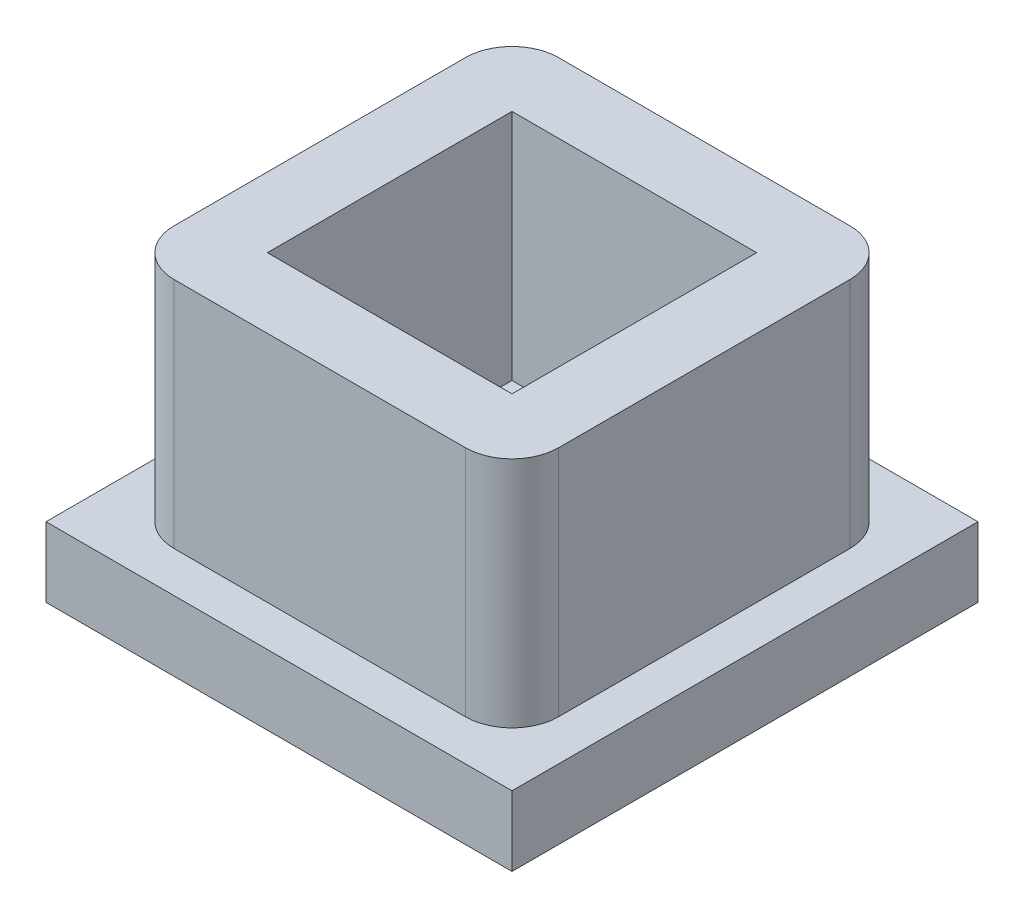
SolidWorks part; units mm, degrees
ref_plane "Front Plane" through (0, 0, 0) normal (0, 0, 1) x (1, 0, 0)
ref_plane "Top Plane" through (0, 0, 0) normal (0, 1, 0) x (1, 0, 0)
ref_plane "Right Plane" through (0, 0, 0) normal (1, 0, 0) x (0, 0, -1)
sketch "Sketch1" plane through (0, 0, 0) normal (0, 1, 0) x (1, 0, 0)
  line L1 (-10, 10) -> (10, 10)
  line L2 (-10, 10) -> (-10, -10)
  line L3 (-10, -10) -> (10, -10)
  line L4 (10, 10) -> (10, -10)
  line L5 (-10, 10) -> (10, -10) construction
  line L6 (-10, -10) -> (10, 10) construction
  point P0 (0, 0)
  dimension "D1" = 20
  dimension "D2" = 20
extrude "Boss-Extrude1" add sketch "Sketch1" along normal blind 3
sketch "Sketch2" plane through (0, 3, 0) normal (0, 1, 0) x (1, 0, 0)
  line L1 (-8.25, 8.25) -> (8.25, 8.25)
  line L2 (-8.25, 8.25) -> (-8.25, -8.25)
  line L3 (-8.25, -8.25) -> (8.25, -8.25)
  line L4 (8.25, 8.25) -> (8.25, -8.25)
  line L5 (-8.25, 8.25) -> (8.25, -8.25) construction
  line L6 (-8.25, -8.25) -> (8.25, 8.25) construction
  line L7 (-5.25, 5.25) -> (5.25, 5.25)
  line L8 (-5.25, 5.25) -> (-5.25, -5.25)
  line L9 (-5.25, -5.25) -> (5.25, -5.25)
  line L10 (5.25, 5.25) -> (5.25, -5.25)
  line L11 (-5.25, 5.25) -> (5.25, -5.25) construction
  line L12 (-5.25, -5.25) -> (5.25, 5.25) construction
  point P0 (0, 0)
  point P6 (0, 0)
  dimension "D1" = 16.5
  dimension "D2" = 16.5
  dimension "D3" = 3
  dimension "D4" = 3
extrude "Boss-Extrude2" add sketch "Sketch2" along normal blind 10
fillet "Fillet1" radius 2 4 edges at (-8.25, 8, 8.25) (8.25, 8, 8.25) (8.25, 8, -8.25) (-8.25, 8, -8.25)
